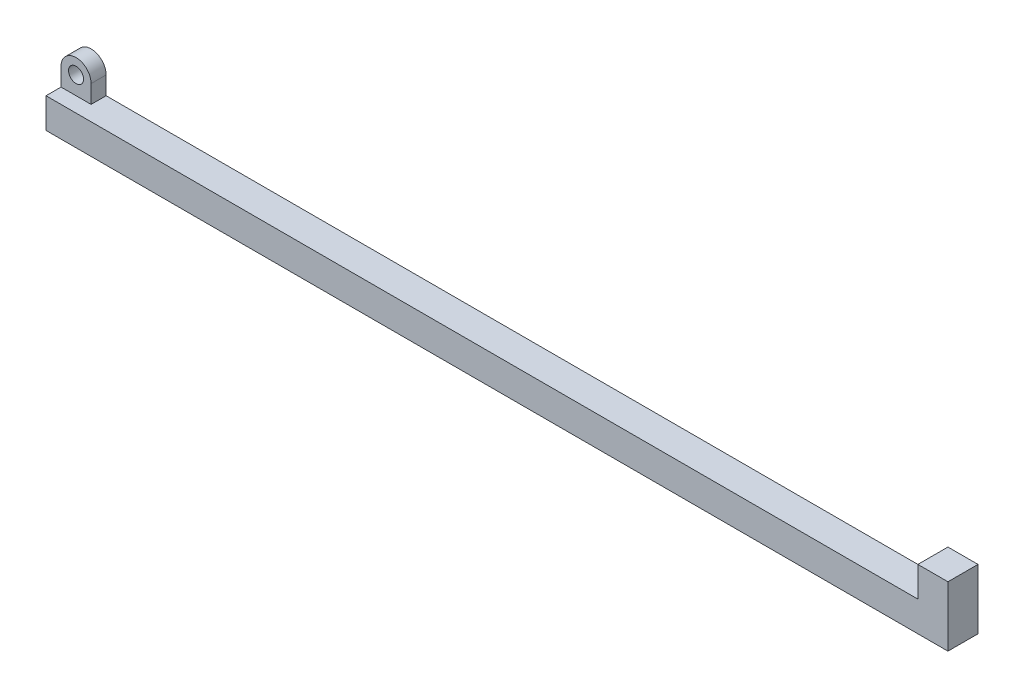
SolidWorks part; units mm, degrees
ref_plane "前视基准面" through (0, 0, 0) normal (0, 0, 1) x (1, 0, 0)
ref_plane "上视基准面" through (0, 0, 0) normal (0, 1, 0) x (1, 0, 0)
ref_plane "右视基准面" through (0, 0, 0) normal (1, 0, 0) x (0, 0, -1)
sketch "草图1" plane through (0, 0, 0) normal (0, 0, 1) x (1, 0, 0)
  line L0 (-50, -160) -> (2950, -160)
  line L1 (50, -60) -> (2850, -60)
  line L2 (50, -60) -> (50, 0)
  line L4 (2850, -60) -> (2850, 40)
  line L5 (2950, -160) -> (2950, 40)
  line L6 (-50, -160) -> (-50, 98.5816) construction
  line L7 (-50, -160) -> (-50, 0)
  line L8 (50, 0) -> (2850, 40) construction
  line L9 (2850, 40) -> (2950, 40)
  line L10 (-50, 98.5816) -> (2950, 141.4388) construction
  line L11 (2950, -160) -> (2950, 141.4388) construction
  circle A0 centre (0, 0) radius 25
  arc A1 (50, 0) -> (-50, 0) centre (0, 0) ccw
  dimension "D4" = 100
  dimension "D6" = 50
  dimension "D1" = 60
  dimension "D2" = 3000
  dimension "D5" = 100
  dimension "D3" = 100
extrude "拉伸1" add sketch "草图1" along normal blind 100
sketch "草图2" plane through (0, 0, 100) normal (0, 0, 1) x (1, 0, 0)
  line L1 (50, -60) -> (-90.943, -60)
  line L2 (50, -60) -> (50, 74.2622)
  line L3 (50, 74.2622) -> (-90.943, 74.2622)
  line L4 (-90.943, -60) -> (-90.943, 74.2622)
extrude "切除-拉伸1" cut sketch "草图2" against normal blind 50
